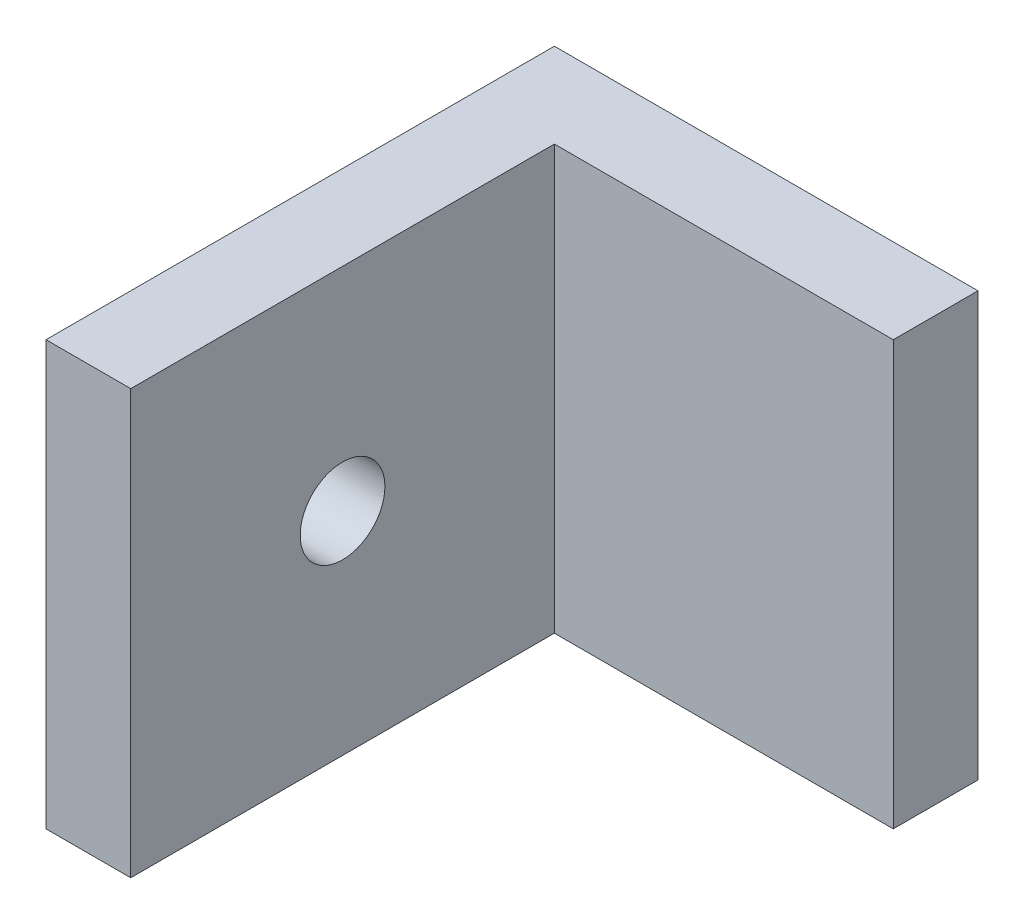
SolidWorks part; units mm, degrees
ref_plane "Front Plane" through (0, 0, 0) normal (0, 0, 1) x (1, 0, 0)
ref_plane "Top Plane" through (0, 0, 0) normal (0, 1, 0) x (1, 0, 0)
ref_plane "Right Plane" through (0, 0, 0) normal (1, 0, 0) x (0, 0, -1)
sketch "Sketch1" plane through (0, 0, 0) normal (0, 0, 1) x (1, 0, 0)
  line L1 (15, -15) -> (-15, -15)
  line L2 (15, -15) -> (15, 15)
  line L3 (15, 15) -> (-15, 15)
  line L4 (-15, -15) -> (-15, 15)
  line L5 (15, -15) -> (-15, 15) construction
  line L6 (15, 15) -> (-15, -15) construction
  point P0 (0, 0)
  dimension "D1" = 30
  dimension "D2" = 30
extrude "Boss-Extrude1" add sketch "Sketch1" along normal blind 6
sketch "Sketch2" plane through (0, 0, 6) normal (0, 0, 1) x (1, 0, 0)
  line L0 (-15, 15) -> (-15, -15) construction
  line L1 (-15, 15) -> (-15, -15)
  line L2 (-9, 15) -> (-9, -15)
  line L3 (-15, 15) -> (-9, 15)
  line L4 (-15, -15) -> (-9, -15)
  dimension "D1" = 6
extrude "Boss-Extrude2" add sketch "Sketch2" along normal blind 30
sketch "Sketch3" plane through (-9, 0, 0) normal (1, 0, 0) x (0, 0, -1)
  line L0 (-36, -15) -> (-36, 15) construction
  line L1 (-36, 15) -> (-6, 15) construction
  circle A0 centre (-21, 0) radius 3
  point P4 (-21, 15)
  dimension "D2" = 6
  dimension "D1" = 15
  dimension "D3" = 15
extrude "Cut-Extrude1" cut sketch "Sketch3" against normal through all
